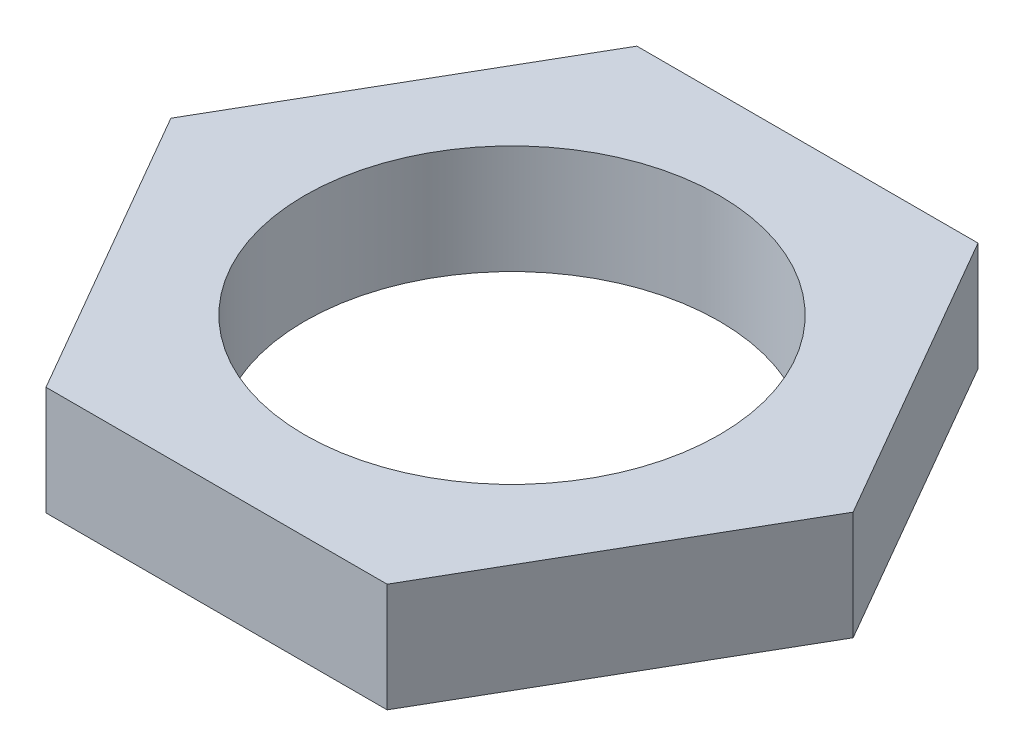
SolidWorks part; units mm, degrees
ref_plane "Front Plane" through (0, 0, 0) normal (0, 0, 1) x (1, 0, 0)
ref_plane "Top Plane" through (0, 0, 0) normal (0, 1, 0) x (1, 0, 0)
ref_plane "Right Plane" through (0, 0, 0) normal (1, 0, 0) x (0, 0, -1)
sketch "Sketch1" plane through (0, 0, 0) normal (0, 1, 0) x (1, 0, 0)
  line L1 (-3.62, -6.27) -> (3.62, -6.27)
  line L2 (3.62, -6.27) -> (7.24, 0)
  line L3 (7.24, 0) -> (3.62, 6.27)
  line L4 (3.62, 6.27) -> (-3.62, 6.27)
  line L5 (-3.62, 6.27) -> (-7.24, 0)
  line L6 (-7.24, 0) -> (-3.62, -6.27)
  circle A0 centre (0, 0) radius 6.27 construction
  circle A1 centre (0, 0) radius 4.4
  dimension "D2" = 8.8
  dimension "D1" = 12.54
extrude "Boss-Extrude1" add sketch "Sketch1" along normal blind 2.31
